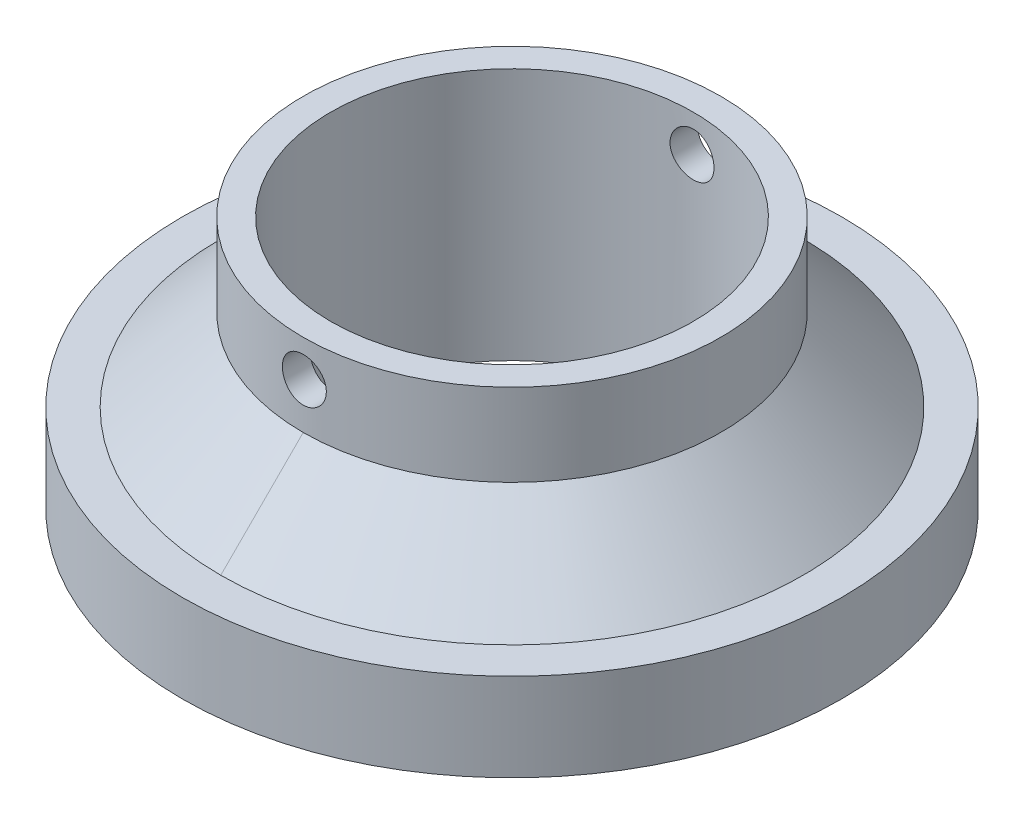
SolidWorks part; units mm, degrees
ref_plane "前视基准面" through (0, 0, 0) normal (0, 0, 1) x (1, 0, 0)
ref_plane "上视基准面" through (0, 0, 0) normal (0, 1, 0) x (1, 0, 0)
ref_plane "右视基准面" through (0, 0, 0) normal (1, 0, 0) x (0, 0, -1)
sketch "草图1" plane through (0, 0, 0) normal (0, 1, 0) x (1, 0, 0)
  circle A0 centre (0, 0) radius 30
extrude "凸台-拉伸1" add sketch "草图1" along normal blind 8
sketch "草图2" plane through (0, 8, 0) normal (0, 1, 0) x (1, 0, 0)
  circle A0 centre (0, 0) radius 16.5
extrude "切除-拉伸1" cut sketch "草图2" against normal blind 8
sketch "草图3" plane through (0, 8, 0) normal (0, 1, 0) x (1, 0, 0)
  circle A0 centre (0, 0) radius 16.5
  circle A1 centre (0, 0) radius 19
extrude "凸台-拉伸2" add sketch "草图3" along normal blind 15
sketch "草图5" plane through (0, 0, 0) normal (0, 0, 1) x (1, 0, 0)
  line L0 (-19, 15.5) -> (-19, 8)
  line L1 (-19, 23) -> (-19, 8) construction
  line L2 (-19, 8) -> (-26.5, 8)
  line L3 (30, 8) -> (-30, 8) construction
  line L4 (-26.5, 8) -> (-19, 15.5)
  point P5 (-19, 15.5)
  point P9 (-25.1862, 8)
  dimension "D1" = 7.5
sweep "扫描1" add profiles "草图5" path edge at (0, 8, 19)
sketch "草图6" plane through (0, 0, 0) normal (0, 0, 1) x (1, 0, 0)
  circle A0 centre (0, 19.6596) radius 2
extrude "切除-拉伸2" cut sketch "草图6" against normal blind 22 and the other way blind 26
